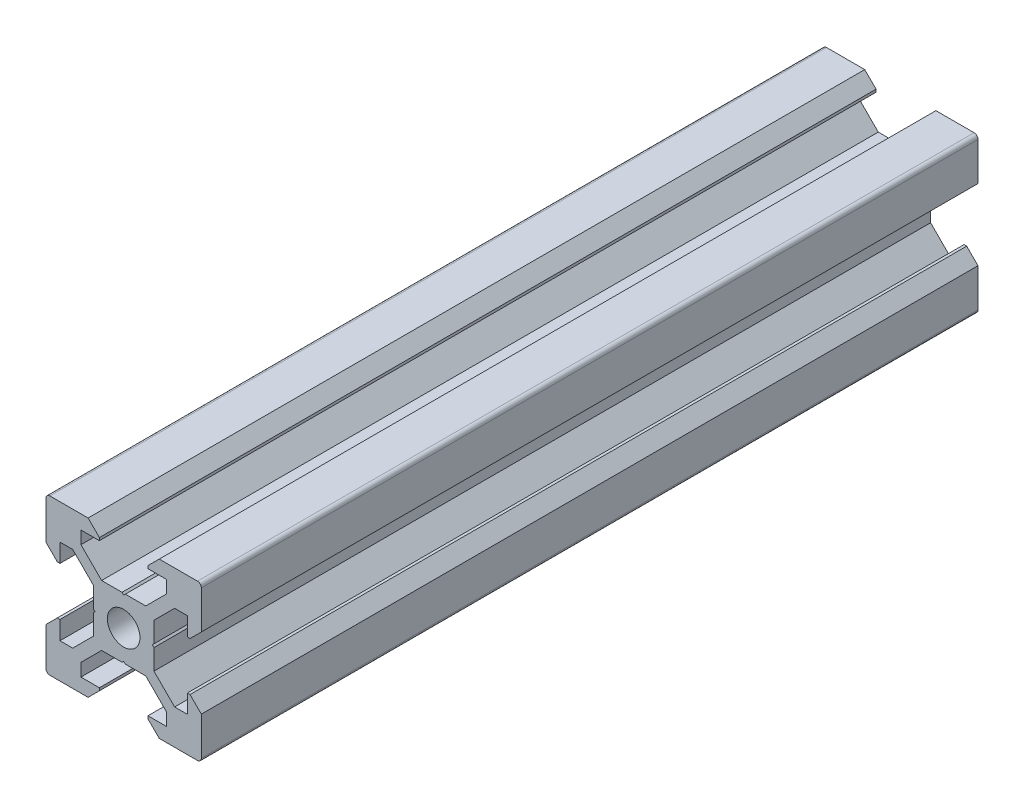
SolidWorks part; units mm, degrees
material "6061-T6 (SS)"
ref_plane "Front Plane" through (0, 0, 0) normal (0, 0, 1) x (1, 0, 0)
ref_plane "Top Plane" through (0, 0, 0) normal (0, 1, 0) x (1, 0, 0)
ref_plane "Right Plane" through (0, 0, 0) normal (1, 0, 0) x (0, 0, -1)
sketch "Sketch1" plane through (0, 0, 0) normal (0, 0, 1) x (1, 0, 0)
  line L1 (9.5, -10) -> (-9.5, -10)
  line L2 (10, -9.5) -> (10, 9.5)
  line L3 (9.5, 10) -> (-9.5, 10)
  line L4 (-10, -9.5) -> (-10, 9.5)
  line L5 (10, -10) -> (-10, 10) construction
  line L6 (10, 10) -> (-10, -10) construction
  circle A0 centre (0, 0) radius 2.1
  arc A1 (-9.5, 10) -> (-10, 9.5) centre (-9.5, 9.5) ccw
  arc A2 (10, 9.5) -> (9.5, 10) centre (9.5, 9.5) ccw
  arc A3 (9.5, -10) -> (10, -9.5) centre (9.5, -9.5) ccw
  arc A4 (-9.5, -10) -> (-10, -9.5) centre (-9.5, -9.5) cw
  point P0 (0, 0)
  line B0 (0, 0) -> (0, 10) construction
  line B1 (0, 3.69) -> (-0.21, 3.9)
  line B2 (-0.21, 3.9) -> (-2.8393, 3.9)
  line B3 (-2.8393, 3.9) -> (-5.5, 6.5607)
  line B4 (-5.5, 6.5607) -> (-5.5, 8.2)
  line B5 (-5.5, 8.2) -> (-3.125, 8.2)
  line B6 (-3.125, 8.2) -> (-3.125, 8.545)
  line B7 (-3.125, 8.545) -> (-4.58, 10)
  line B8 (-4.58, 10) -> (4.58, 10)
  line B9 (0, 0) -> (-5.9132, 5.9132) construction
  line B10 (3.125, 8.545) -> (4.58, 10)
  line B11 (3.125, 8.2) -> (3.125, 8.545)
  line B12 (5.5, 8.2) -> (3.125, 8.2)
  line B13 (5.5, 6.5607) -> (5.5, 8.2)
  line B14 (2.8393, 3.9) -> (5.5, 6.5607)
  line B15 (0.21, 3.9) -> (2.8393, 3.9)
  line B16 (0, 3.69) -> (0.21, 3.9)
  line B17 (0, 0) -> (-10, 0) construction
  line B18 (-3.69, 0) -> (-3.9, -0.21)
  line B19 (-3.9, -0.21) -> (-3.9, -2.8393)
  line B20 (-3.9, -2.8393) -> (-6.5607, -5.5)
  line B21 (-6.5607, -5.5) -> (-8.2, -5.5)
  line B22 (-8.2, -5.5) -> (-8.2, -3.125)
  line B23 (-8.2, -3.125) -> (-8.545, -3.125)
  line B24 (-8.545, -3.125) -> (-10, -4.58)
  line B25 (-10, -4.58) -> (-10, 4.58)
  line B26 (0, 0) -> (-5.9132, -5.9132) construction
  line B27 (-8.545, 3.125) -> (-10, 4.58)
  line B28 (-8.2, 3.125) -> (-8.545, 3.125)
  line B29 (-8.2, 5.5) -> (-8.2, 3.125)
  line B30 (-6.5607, 5.5) -> (-8.2, 5.5)
  line B31 (-3.9, 2.8393) -> (-6.5607, 5.5)
  line B32 (-3.9, 0.21) -> (-3.9, 2.8393)
  line B33 (-3.69, 0) -> (-3.9, 0.21)
  line B34 (0, 0) -> (0, -10) construction
  line B35 (0, -3.69) -> (0.21, -3.9)
  line B36 (0.21, -3.9) -> (2.8393, -3.9)
  line B37 (2.8393, -3.9) -> (5.5, -6.5607)
  line B38 (5.5, -6.5607) -> (5.5, -8.2)
  line B39 (5.5, -8.2) -> (3.125, -8.2)
  line B40 (3.125, -8.2) -> (3.125, -8.545)
  line B41 (3.125, -8.545) -> (4.58, -10)
  line B42 (4.58, -10) -> (-4.58, -10)
  line B43 (0, 0) -> (5.9132, -5.9132) construction
  line B44 (-3.125, -8.545) -> (-4.58, -10)
  line B45 (-3.125, -8.2) -> (-3.125, -8.545)
  line B46 (-5.5, -8.2) -> (-3.125, -8.2)
  line B47 (-5.5, -6.5607) -> (-5.5, -8.2)
  line B48 (-2.8393, -3.9) -> (-5.5, -6.5607)
  line B49 (-0.21, -3.9) -> (-2.8393, -3.9)
  line B50 (0, -3.69) -> (-0.21, -3.9)
  line B51 (0, 0) -> (10, 0) construction
  line B52 (3.69, 0) -> (3.9, 0.21)
  line B53 (3.9, 0.21) -> (3.9, 2.8393)
  line B54 (3.9, 2.8393) -> (6.5607, 5.5)
  line B55 (6.5607, 5.5) -> (8.2, 5.5)
  line B56 (8.2, 5.5) -> (8.2, 3.125)
  line B57 (8.2, 3.125) -> (8.545, 3.125)
  line B58 (8.545, 3.125) -> (10, 4.58)
  line B59 (10, 4.58) -> (10, -4.58)
  line B60 (0, 0) -> (5.9132, 5.9132) construction
  line B61 (8.545, -3.125) -> (10, -4.58)
  line B62 (8.2, -3.125) -> (8.545, -3.125)
  line B63 (8.2, -5.5) -> (8.2, -3.125)
  line B64 (6.5607, -5.5) -> (8.2, -5.5)
  line B65 (3.9, -2.8393) -> (6.5607, -5.5)
  line B66 (3.9, -0.21) -> (3.9, -2.8393)
  line B67 (3.69, 0) -> (3.9, -0.21)
  dimension "D1" = 4.2
  dimension "D3" = 0.5
  dimension "D2" = 20
sketch_block_instance "V Slot 1-4"
sketch_block "V Slot 1" parameters "D1"=10, "D2"=11, "D3"=4.3, "D4"=1.8, "D5"=0.21, "D6"=45, "D7"=9.16, "D8"=1.5, "D9"=6.25
sketch_block_instance "V Slot 1-5"
sketch_block_instance "V Slot 1-6"
sketch_block_instance "V Slot 1-7"
extrude "Boss-Extrude1" add sketch "Sketch1" along normal blind 100 contours B67 B52 B53 B54 B55 B56 B57 B58 L2 A2 L3 B10 B11 B12 B13 B14 B15 B16 B1 B2 B3 B4 B5 B6 B7 A1 L4 B27 B28 B29 B30 B31 B32 B33 B18 B19 B20 B21 B22 B23 B24 A4 L1 B44 B45 B46 B47 B48 B49
